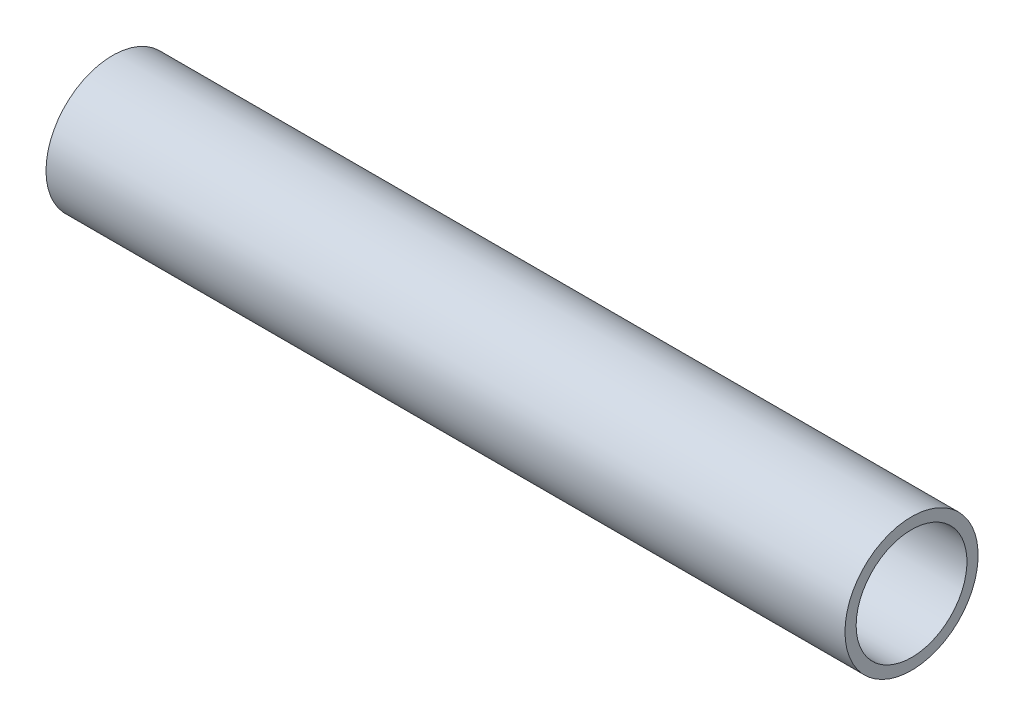
SolidWorks part; units mm, degrees
ref_plane "Front Plane" through (0, 0, 0) normal (0, 0, 1) x (1, 0, 0)
ref_plane "Top Plane" through (0, 0, 0) normal (0, 1, 0) x (1, 0, 0)
ref_plane "Right Plane" through (0, 0, 0) normal (1, 0, 0) x (0, 0, -1)
sketch "Sketch1" plane through (0, 0, 0) normal (0, 0, 1) x (1, 0, 0)
  line L0 (101.4028, 670.0408) -> (25.2028, 670.0408)
  dimension "D1" = 76.2
other "Pipe 0.5 SCH 40(1)"
ref_plane "Plane1" through (101.4028, 670.0408, 0) normal (-1, 0, 0) x (0, -1, 0)
sketch "Sketch11" plane through (101.4028, 670.0408, 0) normal (-1, 0, 0) x (0, -1, 0)
  circle A0 centre (0, 0) radius 5.2832
  circle A1 centre (0, 0) radius 6.35
  point P5 (0, 0)
  dimension "D1" = 12.7
  dimension "D2" = 10.5664
